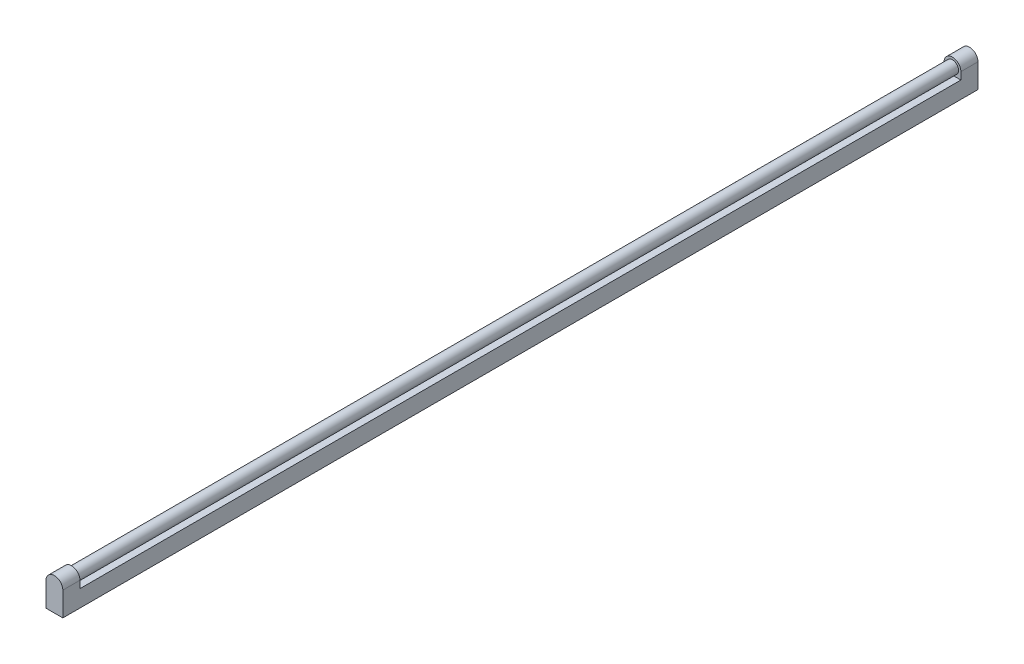
SolidWorks part; units mm, degrees
ref_plane "Front" through (0, 0, 0) normal (0, 0, 1) x (1, 0, 0)
ref_plane "Top" through (0, 0, 0) normal (0, 1, 0) x (1, 0, 0)
ref_plane "Right" through (0, 0, 0) normal (1, 0, 0) x (0, 0, -1)
sketch "Sketch1" plane through (0, 0, 0) normal (0, 0, 1) x (1, 0, 0)
  line L0 (0, 0) -> (21.844, 0)
  line L1 (21.844, 0) -> (21.844, -21.844)
  line L2 (21.844, -21.844) -> (0, -21.844)
  line L3 (0, -21.844) -> (0, 0)
  line L4 (10.922, 0) -> (10.922, 20.32) construction
  line L5 (10.922, 20.32) -> (10.922, 9.398)
  line L6 (21.844, 9.398) -> (21.844, 0)
  line L7 (0, 0) -> (0, 9.398)
  circle A0 centre (10.922, 9.398) radius 10.922
extrude "Boss-Extrude1" add sketch "Sketch1" along normal blind 22.225 contours A0 L7 L0 | L0 L4 L5 A0 | L4 L0 A0 L5 | A0 L0 L6 | L0 A0 | A0 L0 L3 L2 L1
sketch "Sketch2" plane through (0, 0, 0) normal (0, 0, -1) x (-1, 0, 0)
  line L0 (0, -21.844) -> (-21.844, -21.844)
  line L1 (-21.844, -21.844) -> (-21.844, 0)
  line L2 (-21.844, 9.398) -> (-21.844, -21.844) construction
  line L3 (-21.844, 0) -> (0, 0)
  line L4 (0, 0) -> (0, -21.844)
  circle A0 centre (-10.922, 9.398) radius 7.9375
extrude "Boss-Extrude2" add sketch "Sketch2" along normal blind 571.5
mirror "Mirror1" about plane through (0, 0, -571.5) normal (0, 0, 1) of "Boss-Extrude2", "Boss-Extrude1"
sketch "Sketch3" plane through (0, 0, -1143) normal (0, 0, -1) x (-1, 0, 0)
  line L0 (0, -21.844) -> (0, 9.398)
  line L1 (-21.844, -21.844) -> (-21.844, 9.398)
  line L2 (-21.844, -21.844) -> (0, -21.844)
  circle A0 centre (-10.922, 9.398) radius 10.922
  circle M2 centre (-10.922, 9.398) radius 7.9375
extrude "Boss-Extrude3" add sketch "Sketch3" along normal blind 22.225 contours A0 L1 L2 L0 | A0 M2 | M2
